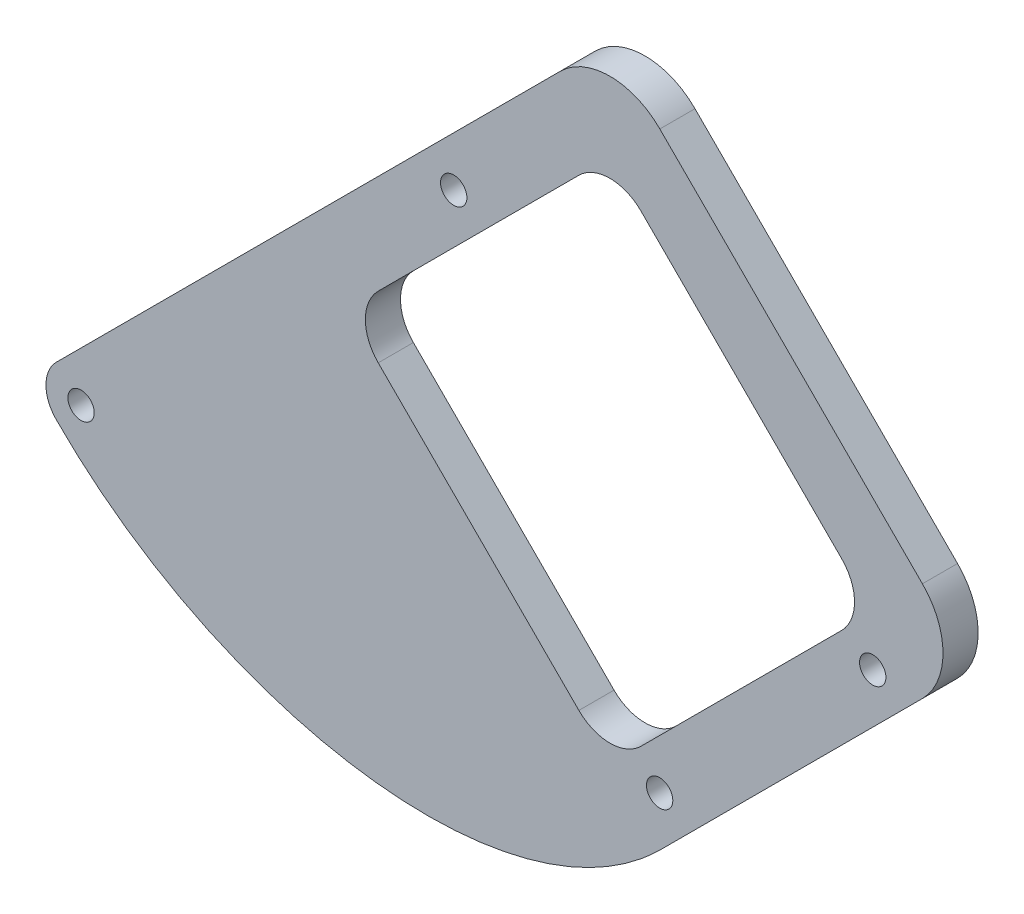
SolidWorks part; units mm, degrees
ref_plane "Front Plane" through (0, 0, 0) normal (0, 0, 1) x (1, 0, 0)
ref_plane "Top Plane" through (0, 0, 0) normal (0, 1, 0) x (1, 0, 0)
ref_plane "Right Plane" through (0, 0, 0) normal (1, 0, 0) x (0, 0, -1)
sketch "Sketch1" plane through (0, 0, 0) normal (0, 0, 1) x (1, 0, 0)
  line L0 (0, -29.9184) -> (0, 29.9184) construction
  line L1 (0, 21.9203) -> (-21.9203, 0) construction
  line L2 (0, 21.9203) -> (21.9203, 0) construction
  line L3 (-21.9203, 0) -> (0, -21.9203) construction
  line L4 (21.9203, 0) -> (0, -21.9203) construction
  line L5 (0, 21.9203) -> (0, -21.9203) construction
  line L6 (-21.9203, 0) -> (21.9203, 0) construction
  line L7 (0, 29.9184) -> (-29.9184, 0) construction
  line L8 (-29.9184, 0) -> (29.9184, 0) construction
  line L9 (0, 29.9184) -> (29.9184, 0) construction
  line L10 (-29.9184, 0) -> (0, -29.9184) construction
  line L11 (29.9184, 0) -> (0, -29.9184) construction
  line L20 (-60.2141, -24.6388) -> (-17.7876, 17.7876) construction
  line L21 (5.6572, -29.9181) -> (29.9181, -5.6572) construction
  line L22 (14.9592, -14.9592) -> (-14.9592, 14.9592) construction
  line L23 (29.9184, 0) -> (0, 29.9184) construction
  line L24 (-20.6161, 20.6161) -> (-63.0425, -21.8103)
  line L25 (-60.2141, -24.6388) -> (-63.0425, -21.8103) construction
  line L26 (32.7465, -8.4857) -> (8.4857, -32.7465)
  line L27 (5.6572, -29.9181) -> (8.4857, -32.7465) construction
  line L28 (29.9181, -5.6572) -> (32.7465, -8.4857) construction
  line L29 (-17.7876, 17.7876) -> (-20.6161, 20.6161) construction
  line L30 (29.9181, -5.6572) -> (32.7465, -2.8288) construction
  line L31 (32.7465, -2.8288) -> (35.5749, -0.0004) construction
  line L32 (27.6871, -2.2313) -> (29.9184, 0) construction
  line L34 (-17.7876, 17.7876) -> (-12.1308, 23.4445) construction
  line L35 (0, 29.9184) -> (-9.3024, 20.6161) construction
  line L36 (-60.2141, -24.6388) -> (-51.897, -16.3217) construction
  line L37 (29.9184, 0) -> (0, -29.9184)
  line L38 (0, -29.9184) -> (-29.9184, 0)
  line L39 (-29.9184, 0) -> (-14.9592, 14.9592)
  line L40 (8.4857, -32.7465) -> (5.6569, -35.5753)
  line L43 (29.9184, 0) -> (0, 29.9184)
  line L44 (0, 29.9184) -> (-14.9592, 14.9592)
  line L45 (32.7465, -8.4857) -> (35.5753, -5.6569)
  line L46 (-20.6161, 20.6161) -> (-5.6335, 35.5986)
  line L48 (5.6802, 35.552) -> (35.5753, 5.6569)
  circle A0 centre (29.9181, -5.6572) radius 1.5
  circle A1 centre (-21.9203, 0) radius 1.5 construction
  circle A2 centre (0, 21.9203) radius 1.5 construction
  circle A3 centre (21.9203, 0) radius 1.5 construction
  circle A7 centre (0, 0) radius 11.5 construction
  circle A9 centre (0, -21.9203) radius 1.5 construction
  circle A10 centre (5.6572, -29.9181) radius 1.5
  circle A11 centre (-17.7876, 17.7876) radius 1.5
  circle A12 centre (-60.2141, -24.6388) radius 1.5
  arc A19 (-63.0425, -21.8103) -> (-63.0425, -27.4672) centre (-60.2141, -24.6388) ccw
  arc A24 (-5.6335, 35.5986) -> (5.6802, 35.552) centre (0, 29.9184) cw
  arc A25 (35.5753, 5.6569) -> (35.5753, -5.6569) centre (29.9184, 0) cw
  spline S0 degree 3 poles (2.2313, -27.6871) (-3.7404, -33.6377) (-44.9588, -32.7004) (-63.0425, -27.4672) knots 0 0 0 0 1 1 1 1 construction
  spline S1 degree 3 poles (-63.0425, -27.4672) (-44.4751, -46.285) (-11.3896, -52.3168) (5.6569, -35.5753) knots 0 0 0 0 1 1 1 1
  point P4 (0, 0)
  point P6 (0, 0)
  point P15 (0, 0)
  point P32 (17.7876, -17.7876)
  point P34 (4.6603, -30.915)
  dimension "D2" = 3
  dimension "D3" = 23
  dimension "D1" = 31
  dimension "D4" = 5.6555
  dimension "D5" = 34.31
  dimension "D6" = 4
  dimension "D7" = 4
  dimension "D8" = 8
  dimension "D9" = 4
  dimension "D10" = 4
  dimension "D11" = 4
  dimension "D12" = 8
  dimension "D13" = 8
  dimension "D14" = 60
extrude "Boss-Extrude1" add sketch "Sketch1" along normal blind 4
fillet "Fillet1" radius 5 4 edges at (0, -29.9184, 2) (-29.9184, 0, 2) (0, 29.9184, 2) (29.9184, 0, 2)
